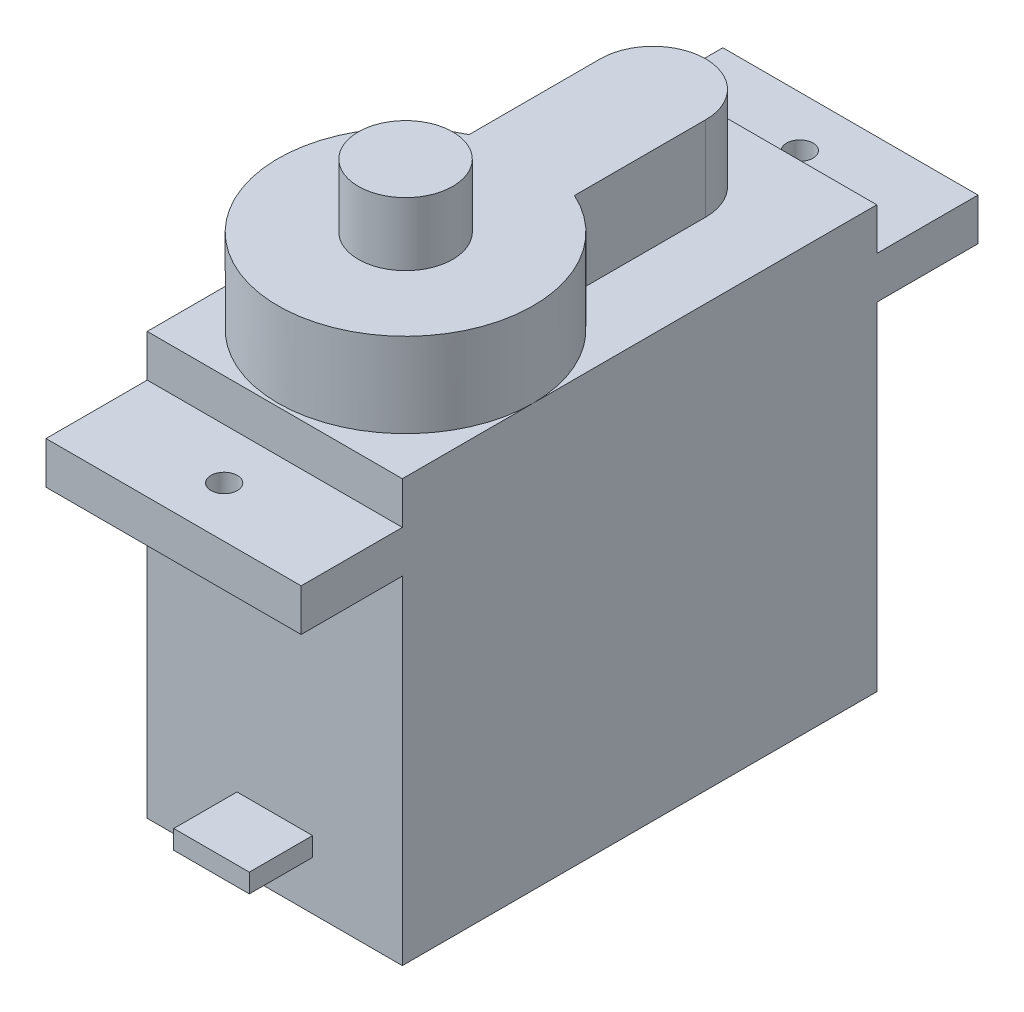
SolidWorks part; units mm, degrees
ref_plane "前视基准面" through (0, 0, 0) normal (0, 0, 1) x (1, 0, 0)
ref_plane "上视基准面" through (0, 0, 0) normal (0, 1, 0) x (1, 0, 0)
ref_plane "右视基准面" through (0, 0, 0) normal (1, 0, 0) x (0, 0, -1)
sketch "草图1" plane through (0, 0, 0) normal (0, 1, 0) x (1, 0, 0)
  line L1 (-0.324, -0.112) -> (11.776, -0.112)
  line L2 (-0.324, -0.112) -> (-0.324, -22.612)
  line L3 (-0.324, -22.612) -> (11.776, -22.612)
  line L4 (11.776, -0.112) -> (11.776, -22.612)
  line L5 (-0.324, -0.112) -> (11.776, -22.612) construction
  line L6 (-0.324, -22.612) -> (11.776, -0.112) construction
  point P4 (5.726, -11.362)
  dimension "D1" = 22.5
  dimension "D2" = 12.1
extrude "凸台-拉伸1" add sketch "草图1" along normal blind 20
sketch "草图2" plane through (0, 0, 22.612) normal (0, 0, 1) x (1, 0, 0)
  line L0 (-0.324, 20) -> (-0.324, 0) construction
  line L1 (-0.324, 18) -> (11.776, 18)
  line L2 (-0.324, 18) -> (-0.324, 16)
  line L3 (-0.324, 16) -> (11.776, 16)
  line L4 (11.776, 18) -> (11.776, 16)
  line L5 (-0.324, 18) -> (11.776, 16) construction
  line L6 (-0.324, 16) -> (11.776, 18) construction
  line L7 (11.776, 20) -> (11.776, 0) construction
  line L8 (-0.324, 20) -> (11.776, 20) construction
  point P4 (5.726, 17)
  dimension "D1" = 2
  dimension "D2" = 2
extrude "凸台-拉伸2" add sketch "草图2" along normal blind 4.8
sketch "草图3" plane through (0, 0, 0.112) normal (0, 0, -1) x (-1, 0, 0)
  line L12 (0.324, 16) -> (0.324, 18)
  line L13 (-11.776, 16) -> (0.324, 16)
  line L14 (-11.776, 18) -> (-11.776, 16)
  line L15 (0.324, 18) -> (-11.776, 18)
  line L16 (0.324, 16) -> (0.324, 18)
  line L17 (-11.776, 16) -> (0.324, 16)
  line L18 (-11.776, 18) -> (-11.776, 16)
  line L19 (0.324, 18) -> (-11.776, 18)
  dimension "D2" = 0
extrude "凸台-拉伸3" add sketch "草图3" along normal blind 4.8
sketch "草图4" plane through (0, 18, 0) normal (0, 1, 0) x (1, 0, 0)
  line L0 (-0.324, 2.288) -> (11.776, 2.288) construction
  line L1 (-0.324, 4.688) -> (-0.324, -0.112) construction
  line L2 (11.776, 4.688) -> (11.776, -0.112) construction
  line L3 (-0.324, -25.012) -> (11.776, -25.012) construction
  line L4 (-0.324, -27.412) -> (-0.324, -22.612) construction
  line L5 (11.776, -27.412) -> (11.776, -22.612) construction
  circle A0 centre (5.726, 2.288) radius 0.625
  circle A1 centre (5.726, -25.012) radius 0.625
  dimension "D1" = 1.25
  dimension "D2" = 1.25
extrude "切除-拉伸1" cut sketch "草图4" against normal through all
sketch "草图5" plane through (0, 20, 0) normal (0, 1, 0) x (1, 0, 0)
  line L0 (5.726, -0.112) -> (5.726, -4.676) construction
  line L1 (11.776, -0.112) -> (-0.324, -0.112) construction
  line L2 (-0.324, -22.612) -> (11.776, -22.612) construction
  line L6 (8.226, -4.676) -> (8.226, -10.9008)
  line L7 (3.226, -4.676) -> (3.226, -10.9008)
  line L8 (5.726, -17.176) -> (5.726, -22.612) construction
  arc A0 (3.226, -10.9008) -> (8.226, -10.9008) centre (5.726, -16.4101) ccw
  arc A3 (8.226, -4.676) -> (3.226, -4.676) centre (5.726, -4.676) ccw
  point P10 (5.726, -9.676)
  dimension "D1" = 5
extrude "凸台-拉伸4" add sketch "草图5" along normal blind 4
sketch "草图6" plane through (0, 24, 0) normal (0, 1, 0) x (1, 0, 0)
  circle A0 centre (5.726, -16.4101) radius 2.2392
extrude "凸台-拉伸5" add sketch "草图6" along normal blind 3
sketch "草图7" plane through (0, 0, 22.612) normal (0, 0, 1) x (1, 0, 0)
  line L0 (5.726, 16) -> (5.726, 0) construction
  line L1 (-0.324, 16) -> (11.776, 16) construction
  line L2 (-0.324, 0) -> (11.776, 0) construction
  line L4 (3.934, 3.2129) -> (7.5181, 3.2129)
  line L5 (3.934, 3.2129) -> (3.934, 2.3169)
  line L6 (3.934, 2.3169) -> (7.5181, 2.3169)
  line L7 (7.5181, 3.2129) -> (7.5181, 2.3169)
  line L8 (5.726, 2.3169) -> (5.726, 3.2129) construction
  line L9 (3.934, 2.7649) -> (7.5181, 2.7649) construction
  point P6 (5.726, 2.7649)
extrude "凸台-拉伸6" add sketch "草图7" along normal blind 3
